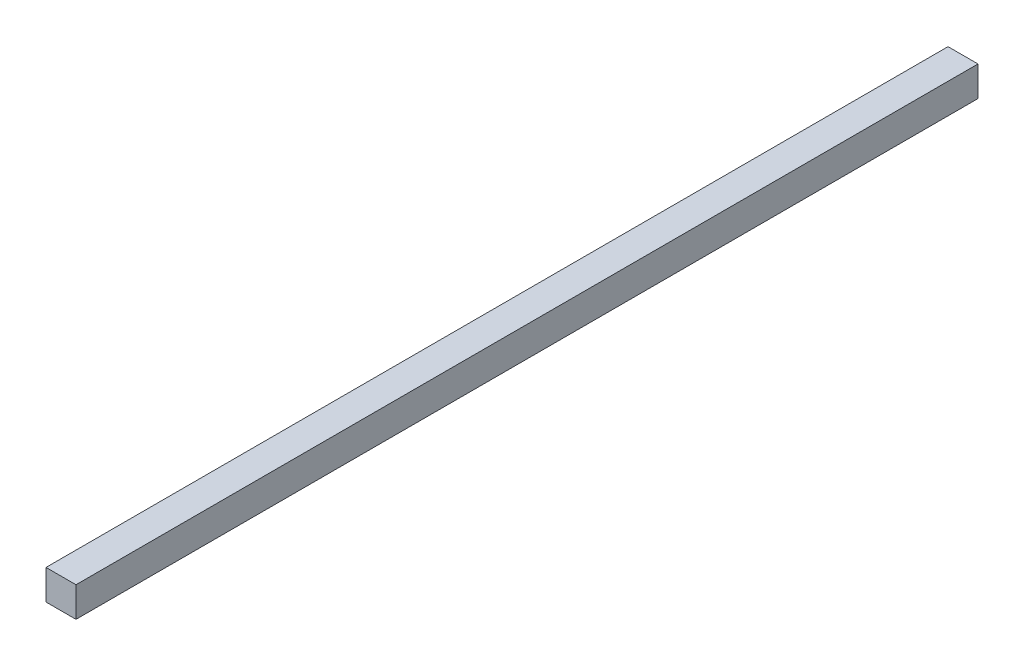
SolidWorks part; units mm, degrees
ref_plane "Plan de face" through (0, 0, 0) normal (0, 0, 1) x (1, 0, 0)
ref_plane "Plan de dessus" through (0, 0, 0) normal (0, 1, 0) x (1, 0, 0)
ref_plane "Plan de droite" through (0, 0, 0) normal (1, 0, 0) x (0, 0, -1)
sketch "Esquisse1" plane through (0, 0, 0) normal (0, 0, 1) x (1, 0, 0)
  line L1 (0, 0) -> (10, 0)
  line L2 (0, 0) -> (0, 10)
  line L3 (0, 10) -> (10, 10)
  line L4 (10, 0) -> (10, 10)
  dimension "D1" = 10
  dimension "D2" = 10
extrude "Boss.-Extru.1" add sketch "Esquisse1" along normal blind 300.81
